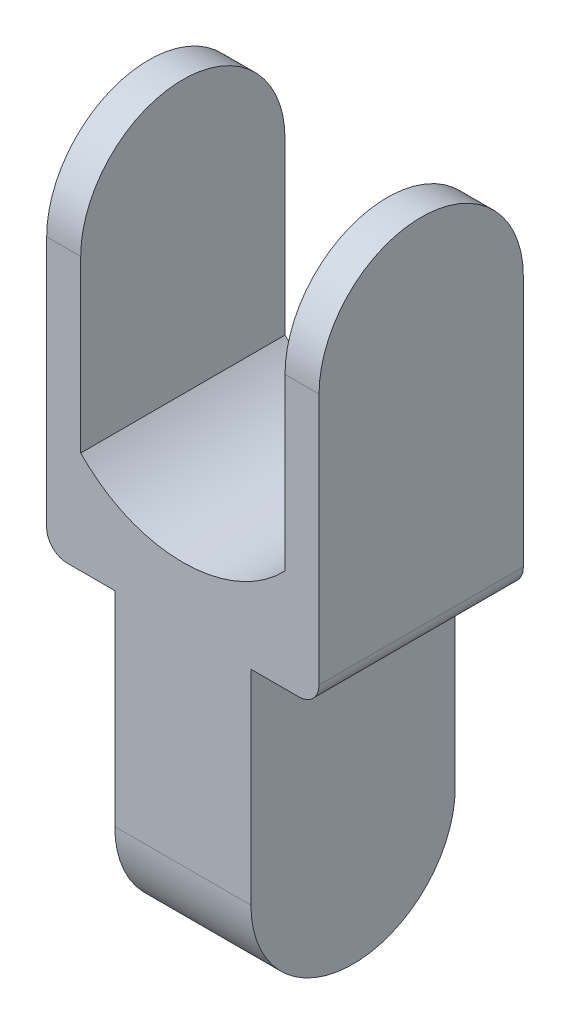
SolidWorks part; units mm, degrees
ref_plane "前视基准面" through (0, 0, 0) normal (0, 0, 1) x (1, 0, 0)
ref_plane "上视基准面" through (0, 0, 0) normal (0, 1, 0) x (1, 0, 0)
ref_plane "右视基准面" through (0, 0, 0) normal (1, 0, 0) x (0, 0, -1)
sketch "草图1" plane through (0, 0, 0) normal (1, 0, 0) x (0, 0, -1)
  circle A0 centre (0, 0) radius 150
extrude "凸台-拉伸1" add sketch "草图1" along normal mid plane 200
sketch "草图2" plane through (0, 0, 0) normal (0, 1, 0) x (1, 0, 0)
  line L1 (-100, 150) -> (100, 150)
  line L2 (-100, 150) -> (-100, -150)
  line L3 (-100, -150) -> (100, -150)
  line L4 (100, 150) -> (100, -150)
  line L5 (-100, 150) -> (100, -150) construction
  line L6 (-100, -150) -> (100, 150) construction
  point P0 (0, 0)
  dimension "D1" = 200
  dimension "D2" = 300
extrude "凸台-拉伸2" add sketch "草图2" along normal blind 300 contours L2 L3 L4 L1
sketch "草图4" plane through (0, 0, 0) normal (0, 0, 1) x (1, 0, 0)
  line L0 (-100, 300) -> (100, 300) construction
  point P0 (0, 300)
sketch "草图5" plane through (0, 0, 0) normal (0, 0, 1) x (1, 0, 0)
  line L1 (0, 300) -> (200, 300)
  line L3 (0, 700) -> (200, 700)
  line L4 (200, 300) -> (200, 700)
  line L5 (0, 300) -> (-200, 300)
  line L7 (0, 700) -> (-200, 700)
  line L8 (-200, 300) -> (-200, 700)
  dimension "D1" = 400
  dimension "D2" = 200
  dimension "D3" = 200
  dimension "D4" = 400
extrude "凸台-拉伸4" add sketch "草图5" along normal mid plane 300 contours L8 L5 L1 L4 L3 L7
sketch "草图6" plane through (0, 0, 0) normal (1, 0, 0) x (0, 0, -1)
  line L0 (-150, 700) -> (150, 700) construction
  circle A0 centre (0, 700) radius 150
extrude "凸台-拉伸5" add sketch "草图6" along normal mid plane 400
sketch "草图7" plane through (0, 0, 0) normal (0, 0, 1) x (1, 0, 0)
  line L0 (200, 850) -> (-200, 850) construction
  line L1 (-150, 1250) -> (150, 1250)
  line L2 (-150, 1250) -> (-150, 450)
  line L3 (-150, 450) -> (150, 450)
  line L4 (150, 1250) -> (150, 450)
  line L5 (-150, 1250) -> (150, 450) construction
  line L6 (-150, 450) -> (150, 1250) construction
  point P0 (0, 850)
  dimension "D1" = 300
  dimension "D2" = 800
extrude "切除-拉伸1" cut sketch "草图7" against normal mid plane 400 contours L2 L3 L4 L1
fillet "圆角1" radius 30 1 edges at (-200, 300, 0)
fillet "圆角2" radius 30 1 edges at (200, 300, 0)
sketch "草图9" plane through (0, 0, 0) normal (0, 0, 1) x (1, 0, 0)
  line L0 (-150, 450) -> (150, 450)
  arc A0 (-150, 450) -> (150, 450) centre (0, 593.5243) ccw
extrude "切除-拉伸3" cut sketch "草图9" against normal mid plane 427
